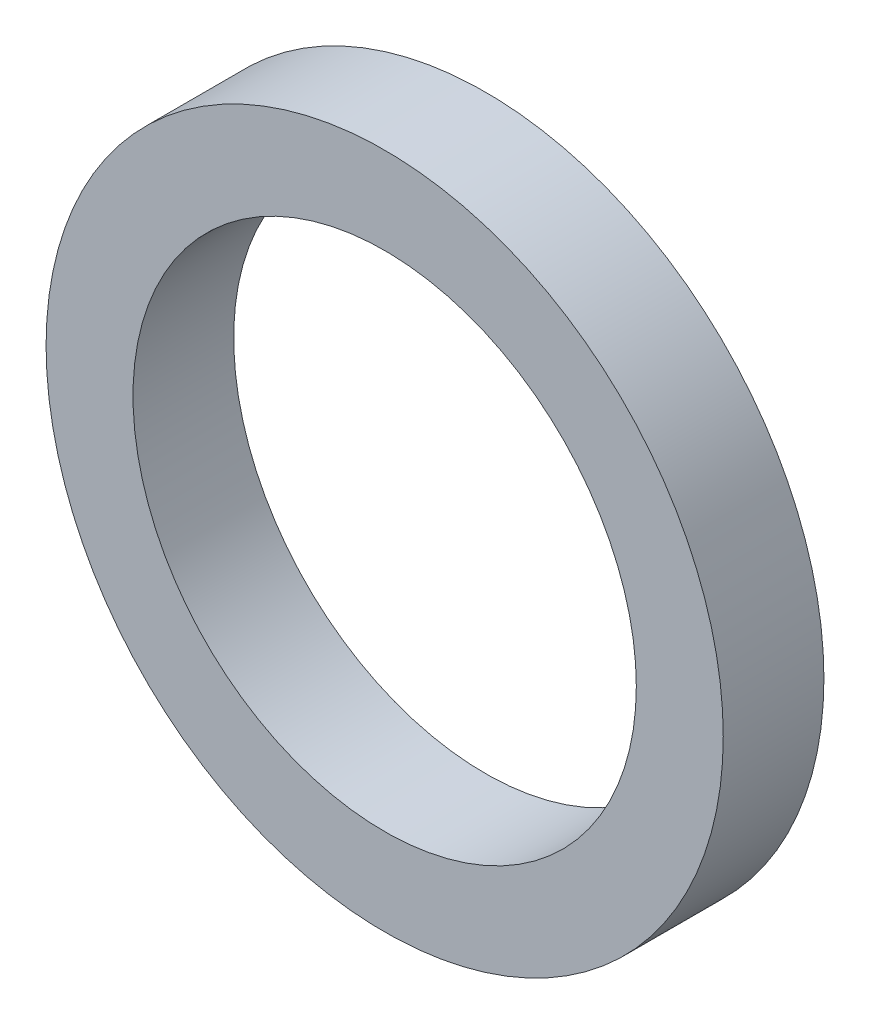
SolidWorks part; units mm, degrees
ref_plane "Front Plane" through (0, 0, 0) normal (0, 0, 1) x (1, 0, 0)
ref_plane "Top Plane" through (0, 0, 0) normal (0, 1, 0) x (1, 0, 0)
ref_plane "Right Plane" through (0, 0, 0) normal (1, 0, 0) x (0, 0, -1)
sketch "Sketch1" plane through (0, 0, 0) normal (0, 0, 1) x (1, 0, 0)
  circle A0 centre (-21.15, -21.15) radius 23.495
  circle A1 centre (-21.15, -21.15) radius 17.4625
  dimension "D1" = 46.99
  dimension "D2" = 34.925
extrude "Boss-Extrude1" add sketch "Sketch1" along normal blind 6.985
